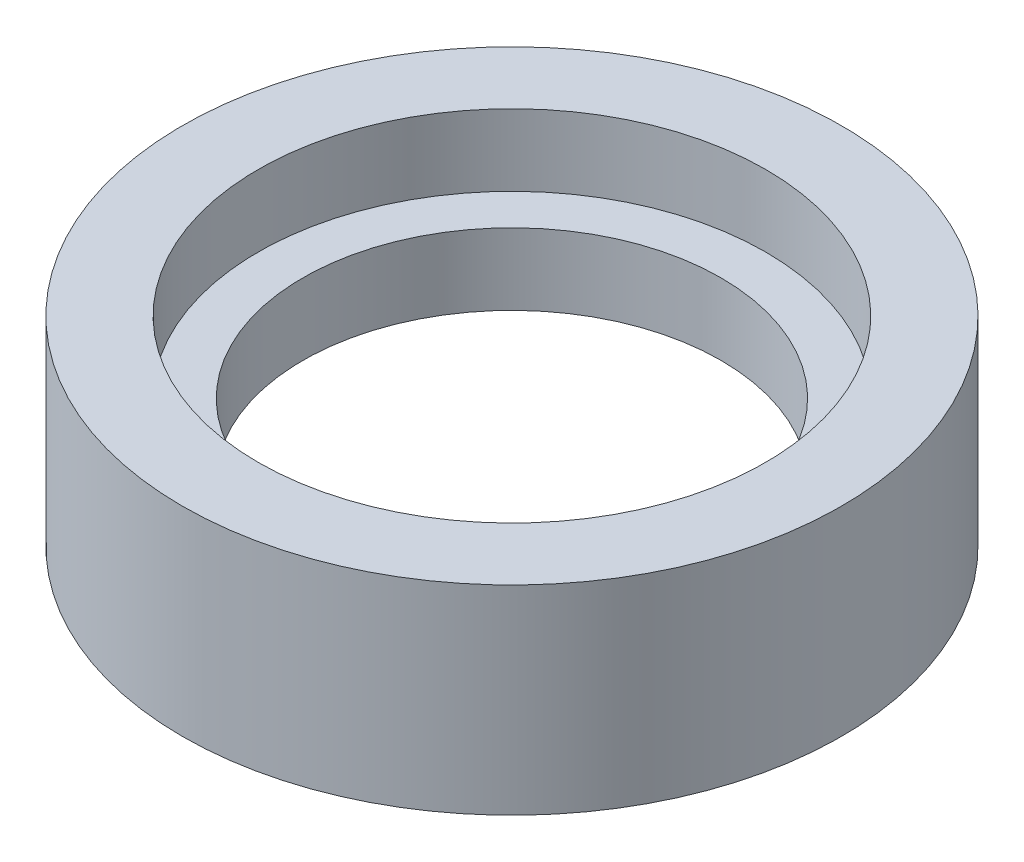
SolidWorks part; units mm, degrees
ref_plane "Front" through (0, 0, 0) normal (0, 0, 1) x (1, 0, 0)
ref_plane "Top" through (0, 0, 0) normal (0, 1, 0) x (1, 0, 0)
ref_plane "Right" through (0, 0, 0) normal (1, 0, 0) x (0, 0, -1)
sketch "Esquisse1" plane through (0, 0, 0) normal (0, 0, 1) x (1, 0, 0)
  line L0 (0, 39.6136) -> (0, -47.4918) construction
  line L1 (-20.459, 0) -> (-20.459, 7)
  line L2 (-20.459, 7) -> (-24.8295, 7)
  line L3 (-24.8295, 7) -> (-24.8295, 14)
  line L4 (-24.8295, 14) -> (-32.25, 14)
  line L5 (-32.25, 14) -> (-32.25, -5.5154)
  line L6 (-32.25, -5.5154) -> (-29.25, -5.5154)
  line L7 (-29.25, -5.5154) -> (-29.25, 0)
  line L8 (-29.25, 0) -> (-20.459, 0)
  dimension "D1" = 3
  dimension "D2" = 58.5
  dimension "D3" = 7
revolve "Révolution1" add sketch "Esquisse1" angle 360 about L0
equation "\"D2@Esquisse1\" = \"D4@Esquisse1@Tas<1>.Part\" + 1.5"
